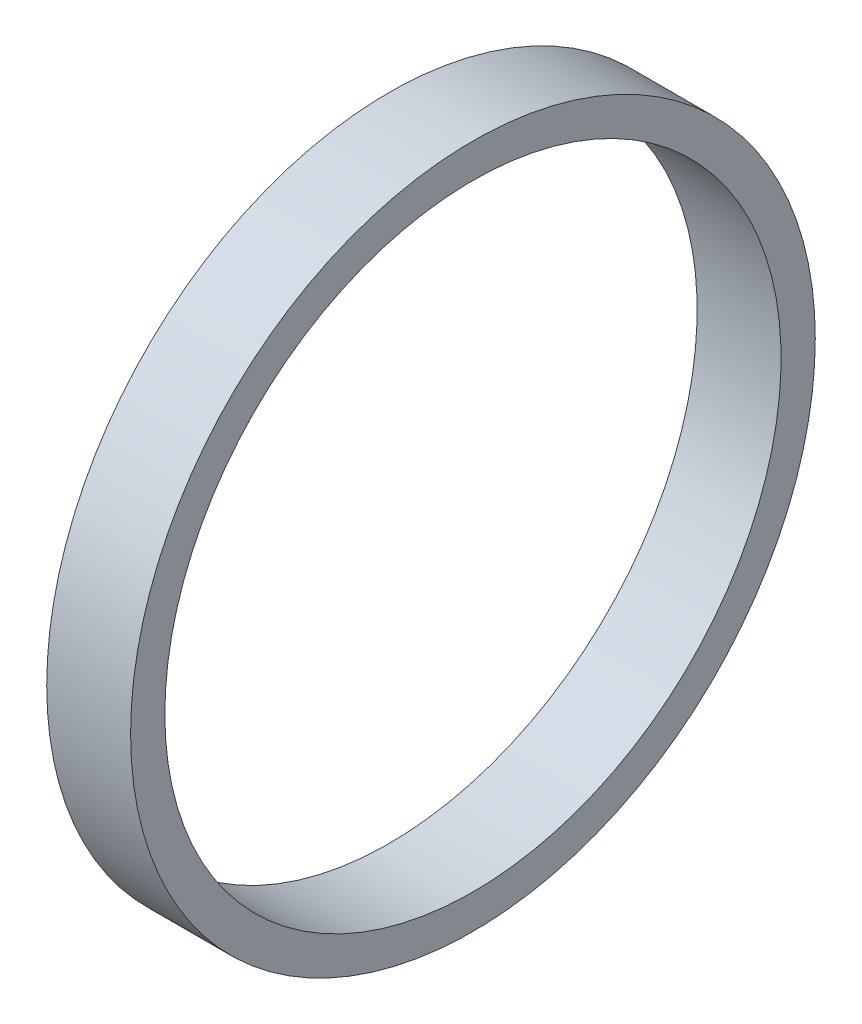
SolidWorks part; units mm, degrees
ref_plane "Front Plane" through (0, 0, 0) normal (0, 0, 1) x (1, 0, 0)
ref_plane "Top Plane" through (0, 0, 0) normal (0, 1, 0) x (1, 0, 0)
ref_plane "Right Plane" through (0, 0, 0) normal (1, 0, 0) x (0, 0, -1)
sketch "Sketch1" plane through (0, 0, 0) normal (0, 0, 1) x (1, 0, 0)
  line L0 (0, 0) -> (0, 90) construction
  line L1 (0, 90) -> (12.25, 90)
  line L2 (0, 90) -> (-12.25, 90)
  line L3 (-12.25, 90) -> (-12.25, 100)
  line L4 (-12.25, 100) -> (12.25, 100)
  line L5 (12.25, 100) -> (12.25, 90)
  line L6 (0, 0) -> (75.874, 0) construction
  dimension "D1" = 90
  dimension "D2" = 10
  dimension "D3" = 12.25
  dimension "D4" = 12.25
revolve "Revolve1" add sketch "Sketch1" angle 360 about L6
